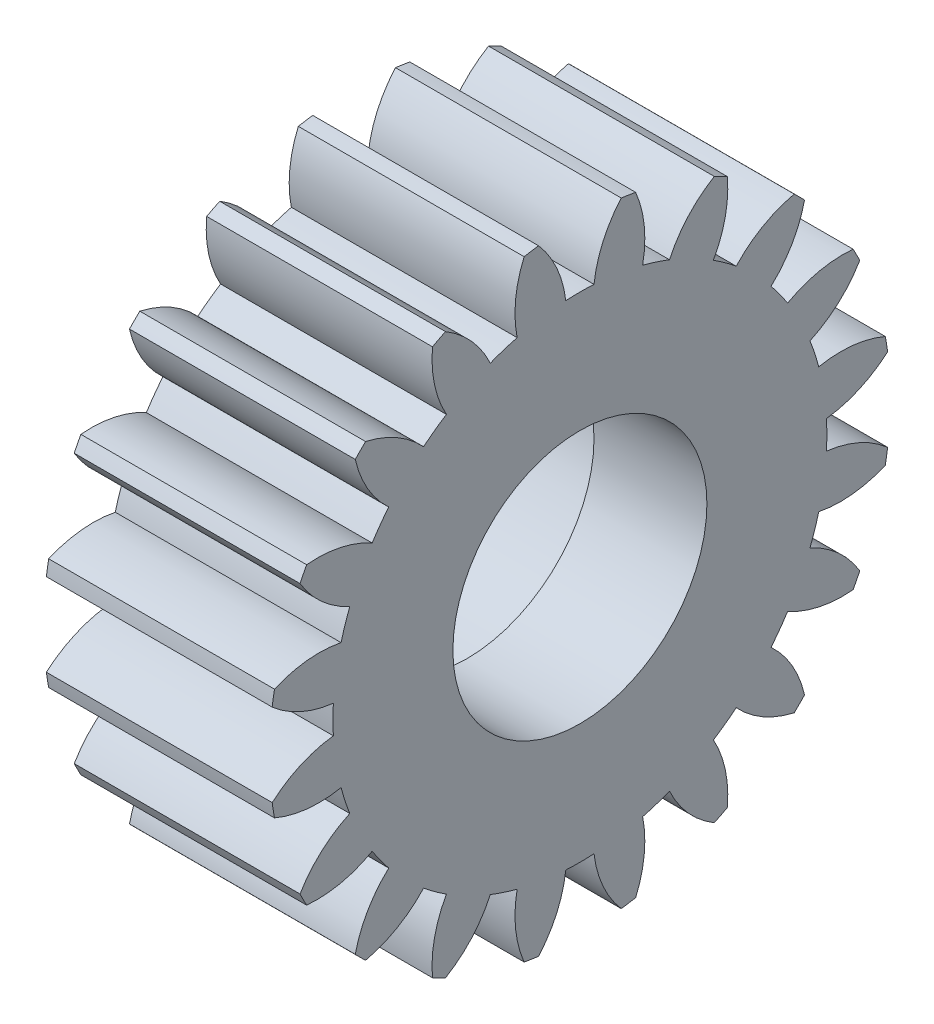
SolidWorks part; units mm, degrees
ref_plane "Plane1" through (0, 0, 0) normal (0, 0, 1) x (1, 0, 0)
ref_plane "Plane2" through (0, 0, 0) normal (0, 1, 0) x (1, 0, 0)
ref_plane "Plane3" through (0, 0, 0) normal (1, 0, 0) x (0, 0, -1)
sketch "HoldingSke" plane through (0, 0, 0) normal (0, 1, 0) x (1, 0, 0)
  line L0 (0, 0) -> (0.9397, -0.342)
  line L1 (-15, 0) -> (100, 0) construction
  line L2 (0, 0) -> (-2.1039, 2.3779)
  line L3 (0, 0) -> (-11.863, 4.5341)
  line L4 (0, 0) -> (8.1152, 2.9537)
  line L5 (0, 0) -> (-46.8476, -17.4728)
  line L6 (0, 0) -> (-8.2896, -5.593)
  line L7 (-2.1039, 2.3779) -> (8.6586, 51.2059)
  line L8 (-76.2, 54.61) -> (-75.3, 54.61)
  line L9 (-71.009, 38.7566) -> (-53.1078, 45.2721)
  line L10 (-76.2, 71.12) -> (104.1128, 71.12)
  line L11 (0, 0) -> (-10, 0)
  line L12 (-76.2, 101.6) -> (-76.162, 101.6)
  line L13 (24.9733, 27.94) -> (52.9518, 28.4284)
  line L14 (24.9733, 27.94) -> (24.9743, 27.94)
  line L15 (24.9733, 27.94) -> (100.4006, 29.5858)
  line L16 (-63.627, -1) -> (-12.827, -1)
  circle A0 centre (0, 0) radius 2.5
  circle A1 centre (0, 0) radius 8.749
  circle A2 centre (0, 0) radius 37.5
  circle A3 centre (0, 0) radius 2.5
  dimension "MHD" = 17.498
  dimension "Hub_dia" = 75
  dimension "Bore" = 5
  dimension "MBD" = 5
  dimension "Num_teeth" = 20
  dimension "Pitch" = 1
  dimension "Overall_len" = 50
  dimension "Show_teeth" = 20
  dimension "Thickness" = 10
  dimension "OAL" = 50.0001
  dimension "T_dim" = 0.9
  dimension "Ap" = 20
  dimension "H" = 19.05
  dimension "Pitch_radius" = 180.3128
  dimension "Width" = 10
  dimension "Backlash" = 0.038
  dimension "Addendum_fac" = 1
  dimension "Dedendum_fac" = 1.25
  dimension "Clearance_fac" = 0.25
  dimension "Dedendum_add" = 0.001
  dimension "Module" = 1
sketch "BasProSke" plane through (0, 0, 0) normal (0, 1, 0) x (1, 0, 0)
  line L0 (-10, 0) -> (60, 0) construction
  line L1 (0, 0) -> (0, 11)
  line L2 (0, 0) -> (10, 0)
  line L3 (10, 0) -> (10, 11)
  line L4 (10, 11) -> (0, 11)
  dimension "Thickness" = 10
  dimension "Diameter" = 22
revolve "Base-Revolve" add sketch "BasProSke" angle 360 about L0
sketch "TooCutSke" plane through (0, 0, 0) normal (1, 0, 0) x (0, 0, -1)
  line L1 (0, 0) -> (0, 107) construction
  line L2 (0, 0) -> (-0.8511, 9.9637) construction
  line L3 (0, 0) -> (-3.1206, 19.7028) construction
  line L4 (-0.8511, 9.9637) -> (-1.5603, 9.8514) construction
  arc A0 (0.4999, 8.7347) -> (-0.4999, 8.7347) centre (0, 0) ccw
  arc A1 (1.4852, 10.9249) -> (-1.4852, 10.9249) centre (0, 0) ccw
  circle A2 centre (0, 0) radius 10 construction
  circle A3 centre (0, 0) radius 9.3969 construction
  arc A4 (-0.4999, 8.7347) -> (-1.4852, 10.9249) centre (-4.4722, 8.2645) ccw
  arc A5 (1.4852, 10.9249) -> (0.4999, 8.7347) centre (4.4722, 8.2645) ccw
  dimension "Root_dia" = 17.498
  dimension "Overcut_dia" = 22.0508
  dimension "Pitch_dia" = 20
  dimension "Base_dia" = 18.7939
  dimension "Flank_rad" = 4
  dimension "Half_ang" = 9
  dimension "Half_CT" = 0.7181
extrude "ToothCut" cut sketch "TooCutSke" along normal through all
fillet "Breaks" [suppressed] radius 0.02
fillet "RootFillets" [suppressed] radius 0.251
pattern_circular "TeethCuts" count 20 every 18 about axis through (-10, 0, 0) along (1, 0, 0) of "ToothCut", "RootFillets", "Breaks"
sketch "HubNeaOneSke" plane through (0, 0, 0) normal (-1, 0, 0) x (0, 0, 1)
  circle A0 centre (0, 0) radius 8.749
  dimension "Diameter" = 17.498
extrude "HubNearOne" [suppressed] add sketch "HubNeaOneSke" along normal blind 40.0001
sketch "HubNeaBotSke" plane through (0, 0, 0) normal (-1, 0, 0) x (0, 0, 1)
  circle A0 centre (0, 0) radius 8.749
  dimension "Diameter" = 17.498
extrude "HubNearBoth" [suppressed] add sketch "HubNeaBotSke" along normal blind 20
ref_plane "FarPln" through (10, 0, 0) normal (1, 0, 0) x (0, 0, -1)
sketch "HubFarSke" plane through (10, 0, 0) normal (1, 0, 0) x (0, 0, -1)
  circle A0 centre (0, 0) radius 8.749
  dimension "Diameter" = 17.498
extrude "HubFar" [suppressed] add sketch "HubFarSke" along normal blind 20
sketch "BorSke" plane through (0, 0, 0) normal (1, 0, 0) x (0, 0, -1)
  circle A0 centre (0, 0) radius 2.5
  dimension "Diameter" = 5
extrude "Bore" cut sketch "BorSke" along normal mid plane 100.0001
sketch "KeySke" plane through (0, 0, 0) normal (1, 0, 0) x (0, 0, -1)
  line L0 (-1, 0) -> (-1, 3.4)
  line L1 (-1, 3.4) -> (1, 3.4)
  line L2 (1, 3.4) -> (1, 0)
  line L3 (0, 0) -> (0, 34) construction
  line L4 (-1, 0) -> (1, 0)
  dimension "Offset" = 3.4
  dimension "Width" = 2
extrude "Keyway" [suppressed] cut sketch "KeySke" along normal mid plane 100.0001
pattern_circular "Keyway2" [suppressed] count 2 every 90 about axis through (-10, 0, 0) along (1, 0, 0)
sketch "Sketch1" plane through (0, 0, 0) normal (-1, 0, 0) x (0, 0, 1)
  circle A0 centre (0, 0) radius 6.1
extrude "Cut-Extrude1" cut sketch "Sketch1" against normal blind 4
sketch "Sketch2" plane through (10, 0, 0) normal (1, 0, 0) x (0, 0, -1)
  circle A0 centre (0, 0) radius 4.5
extrude "Cut-Extrude2" cut sketch "Sketch2" against normal through all
sketch "Sketch3" plane through (10, 0, 0) normal (1, 0, 0) x (0, 0, -1)
  circle A0 centre (0, 0) radius 14.8984
extrude "Cut-Extrude3" cut sketch "Sketch3" against normal blind 2
equation "' \"Module@HoldingSke\" = 6.35"
equation "' \"Num_teeth@HoldingSke\" = 12"
equation "' \"Ap@HoldingSke\" =  20"
equation "' \"Ap@HoldingSke\" = 20"
equation "' \"Width@HoldingSke\" = 0.5 * 25.4"
equation "' \"Hub_dia@HoldingSke\"= 1 * 25.4"
equation "' \"Hub_dia@HoldingSke\" = 1 * 25.4"
equation "' \"Overall_len@HoldingSke\" = 1.0 * 25.4"
equation "' \"Bore@HoldingSke\" = 0.75 * 25.4"
equation "' \"T_dim@HoldingSke\" = 0.1 * 25.4"
equation "' \"Width@KeySke\" = 0.25 * 25.4"
equation "' \"Show_teeth@HoldingSke\" = 13"
equation "' \"Backlash@HoldingSke\" = 0.009 * 25.4"
equation "' \"Addendum_fac@HoldingSke\" = 1.0"
equation "' \"Dedendum_fac@HoldingSke\" = 1.25"
equation "' \"Dedendum_add@HoldingSke\" = 0.00005 * 25.4"
equation "' \"Clearance_fac@HoldingSke\" = 0.25"
equation "\"Pitch@HoldingSke\" = 1 / \"Module@HoldingSke\""
equation "\"Overcut_dia@TooCutSke\" = (\"Num_teeth@HoldingSke\" + 2 * \"Addendum_fac@HoldingSke\") / \"Pitch@HoldingSke\" + 0.002 * 25.4"
equation "\"Pitch_dia@TooCutSke\" = \"Num_teeth@HoldingSke\" / \"Pitch@HoldingSke\""
equation "\"Base_dia@TooCutSke\" = \"Num_teeth@HoldingSke\" / \"Pitch@HoldingSke\" * cos((\"Ap@HoldingSke\"  * 3.14159265 / 180))"
equation "\"Root_dia@TooCutSke\" = (\"Num_teeth@HoldingSke\" + 2) / \"Pitch@HoldingSke\" - 2 * (\"Addendum_fac@HoldingSke\" + \"Dedendum_fac@HoldingSke\") / \"Pitch@HoldingSke\" - \"Dedendum_add@HoldingSke\" * 2"
equation "\"Half_ang@TooCutSke\" = 180 / \"Num_teeth@HoldingSke\""
equation "\"Half_CT@TooCutSke\" = \"Num_teeth@HoldingSke\" / \"Pitch@HoldingSke\" * sin((3.14159265 / 2 / \"Num_teeth@HoldingSke\")) / 2 - 7 * \"Backlash@HoldingSke\" / 4"
equation "\"Flank_rad@TooCutSke\" = \"Num_teeth@HoldingSke\" / \"Pitch@HoldingSke\" / 5"
equation "\"Radius@RootFillets\" = \"Clearance_fac@HoldingSke\" / \"Pitch@HoldingSke\" + \"Dedendum_add@HoldingSke\""
equation "\"Break_rad@Breaks\" = 0.02 / \"Pitch@HoldingSke\""
equation "\"Thickness@HoldingSke\" = \"Width@HoldingSke\""
equation "\"OAL@HoldingSke\" = \"Thickness@HoldingSke\""
equation "\"MHD@HoldingSke\" = (\"Num_teeth@HoldingSke\" + 2) / \"Pitch@HoldingSke\" - 2 * (\"Addendum_fac@HoldingSke\" + \"Dedendum_fac@HoldingSke\")  / \"Pitch@HoldingSke\" - \"Dedendum_add@HoldingSke\" * 2"
equation "\"MBD@HoldingSke\" = (\"Num_teeth@HoldingSke\" + 2) / \"Pitch@HoldingSke\" - 2 * (\"Addendum_fac@HoldingSke\" + \"Dedendum_fac@HoldingSke\")  / \"Pitch@HoldingSke\" - \"Dedendum_add@HoldingSke\" * 2 - 0.002 * 25.4"
equation "\"MHD@HoldingSke\" = ((sgn( \"MHD@HoldingSke\" - \"Hub_dia@HoldingSke\" )-1)*( \"MHD@HoldingSke\" - \"Hub_dia@HoldingSke\" ))/-2+ \"Hub_dia@HoldingSke\""
equation "\"MBD@HoldingSke\" = ((sgn( \"MBD@HoldingSke\" - \"Bore@HoldingSke\" )-1)*( \"MBD@HoldingSke\" - \"Bore@HoldingSke\" ))/-2+ \"Bore@HoldingSke\""
equation "\"OAL@HoldingSke\" = ((sgn( \"OAL@HoldingSke\" - \"Overall_len@HoldingSke\" )+1)*( \"OAL@HoldingSke\" - \"Overall_len@HoldingSke\" ))/2 + \"Overall_len@HoldingSke\" + 0.000002 * 25.4"
equation "\"Num_teeth@TeethCuts\" = int( \"Show_teeth@HoldingSke\" ) + 1"
equation "\"Num_teeth@TeethCuts\" = ((sgn( \"Num_teeth@TeethCuts\" - \"Num_teeth@HoldingSke\" )-1)*( \"Num_teeth@TeethCuts\" - \"Num_teeth@HoldingSke\" ))/-2+ \"Num_teeth@HoldingSke\""
equation "\"Num_teeth@TeethCuts\" = ((sgn( \"Num_teeth@TeethCuts\" - 2.0)+1)*( \"Num_teeth@TeethCuts\" - 2.0))/2 +2.0"
equation "\"Angle@TeethCuts\" = 360.0 / \"Num_teeth@HoldingSke\""
equation "\"Diameter@BasProSke\" = (\"Num_teeth@HoldingSke\" + 2 * \"Addendum_fac@HoldingSke\") / \"Pitch@HoldingSke\""
equation "\"Thickness@BasProSke\"  = \"Thickness@HoldingSke\""
equation "' \"Fillet_rad@BasProSke\" =  \"Thickness@HoldingSke\" * 0.05"
equation "' \"Fillet_rad@BasProSke\" = \"Thickness@HoldingSke\" * 0.05"
equation "\"MHD@HoldingSke\" = ((sgn( \"MHD@HoldingSke\" - \"Root_dia@TooCutSke\" )-1)*( \"MHD@HoldingSke\" - \"Root_dia@TooCutSke\" ))/-2+ \"Root_dia@TooCutSke\""
equation "\"Diameter@HubNeaOneSke\" = \"MHD@HoldingSke\""
equation "\"Length@HubNearOne\" = \"OAL@HoldingSke\" - \"Thickness@BasProSke\""
equation "\"Diameter@HubNeaBotSke\" = \"MHD@HoldingSke\""
equation "\"Length@HubNearBoth\" = ( \"OAL@HoldingSke\" - \"Thickness@BasProSke\" ) / 2.0"
equation "\"Thickness@FarPln\" = \"Thickness@BasProSke\""
equation "\"Diameter@HubFarSke\" = \"MHD@HoldingSke\""
equation "\"Length@HubFar\" = ( \"OAL@HoldingSke\" - \"Thickness@BasProSke\" ) / 2.0"
equation "\"Diameter@BorSke\" = \"MBD@HoldingSke\""
equation "\"D1@Bore\" = \"OAL@HoldingSke\" * 2.0"
equation "\"D1@Keyway\" = \"OAL@HoldingSke\" * 2.0"
equation "\"Offset@KeySke\" = \"T_dim@HoldingSke\" + \"MBD@HoldingSke\" / 2.0"
